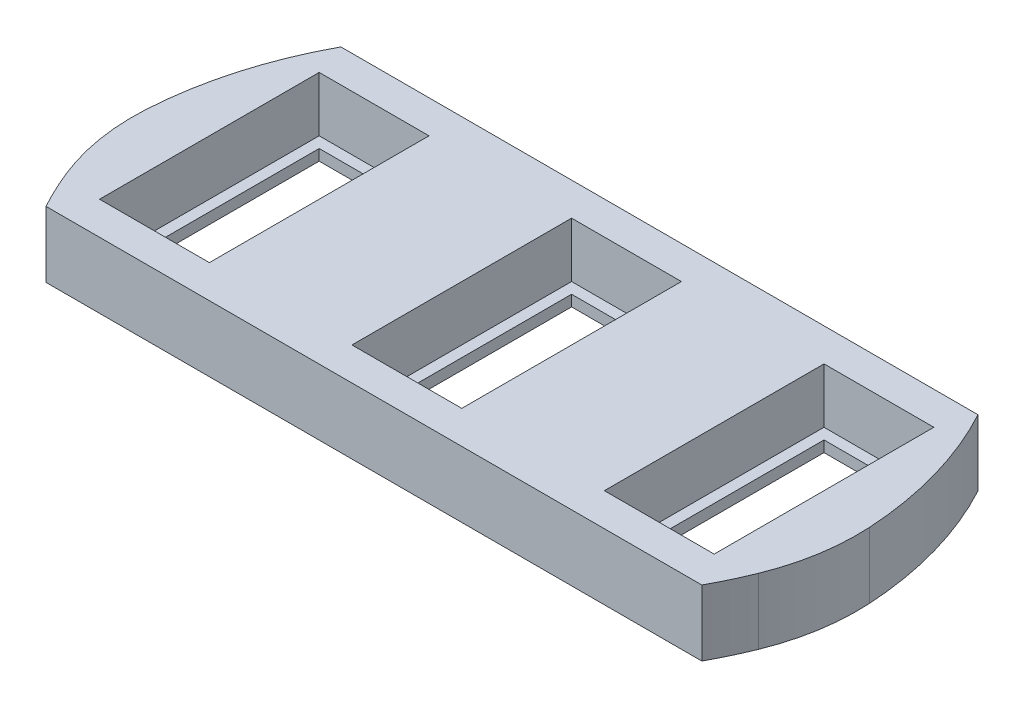
SolidWorks part; units mm, degrees
ref_plane "Plan de face" through (0, 0, 0) normal (0, 0, 1) x (1, 0, 0)
ref_plane "Plan de dessus" through (0, 0, 0) normal (0, 1, 0) x (1, 0, 0)
ref_plane "Plan de droite" through (0, 0, 0) normal (1, 0, 0) x (0, 0, -1)
sketch "Esquisse1" plane through (0, 0, 0) normal (0, 1, 0) x (1, 0, 0)
  line L0 (0, 30.5) -> (0, -31.5) construction
  line L1 (29.005, 12.7388) -> (-29.005, 12.7388)
  line L2 (-29.8592, -13.2612) -> (29.8592, -13.2612)
  line L3 (26.9834, 8.7388) -> (26.9834, -9.2612)
  line L4 (-27.9834, 9.7388) -> (-17.9834, 9.7388) construction
  line L5 (-27.9834, 9.7388) -> (-27.9834, -10.2612) construction
  line L6 (-27.9834, -10.2612) -> (-17.9834, -10.2612) construction
  line L7 (-17.9834, 9.7388) -> (-17.9834, -10.2612) construction
  line L8 (-27.9834, 9.7388) -> (-30.9834, 9.7388) construction
  line L9 (-5, 9.7388) -> (5, 9.7388) construction
  line L10 (-26.9834, 8.7388) -> (-18.9834, 8.7388)
  line L11 (-5, 9.7388) -> (-5, -10.2612) construction
  line L12 (-5, -10.2612) -> (5, -10.2612) construction
  line L13 (5, 9.7388) -> (5, -10.2612) construction
  line L14 (-26.9834, 8.7388) -> (-26.9834, -9.2612)
  line L15 (-26.9834, -9.2612) -> (-18.9834, -9.2612)
  line L16 (-18.9834, 8.7388) -> (-18.9834, -9.2612)
  line L17 (4, 8.7388) -> (-4, 8.7388)
  line L18 (26.9834, 8.7388) -> (18.9834, 8.7388)
  line L19 (4, -9.2612) -> (-4, -9.2612)
  line L20 (-4, 8.7388) -> (-4, -9.2612)
  line L21 (18.9834, 8.7388) -> (18.9834, -9.2612)
  line L22 (26.9834, -9.2612) -> (18.9834, -9.2612)
  line L23 (4, 8.7388) -> (4, -9.2612)
  arc A0 (33.4591, -1.3457) -> (-33.4591, -1.3457) centre (0, -3) ccw construction
  arc A1 (-32.0815, -9.6897) -> (32.0815, -9.6897) centre (0, 3) ccw construction
  arc A2 (-32.0815, -9.6897) -> (-33.4591, -1.3457) centre (-13.4835, -2.3333) cw construction
  arc A3 (32.0815, -9.6897) -> (33.4591, -1.3457) centre (13.4835, -2.3333) ccw construction
  arc A4 (-31.5188, -9.75) -> (-29.8592, -13.2612) centre (0, 3) ccw
  arc A5 (29.005, 12.7388) -> (32.945, -1.0962) centre (0, -3) cw
  arc A6 (-32.945, -1.0962) -> (-31.5188, -9.75) centre (-12.9783, -2.25) ccw
  arc A7 (32.945, -1.0962) -> (31.5188, -9.75) centre (12.9783, -2.25) cw
  arc A8 (-29.005, 12.7388) -> (-32.945, -1.0962) centre (0, -3) ccw
  arc A9 (31.5188, -9.75) -> (29.8592, -13.2612) centre (0, 3) cw
  point P10 (0, -31.5)
  point P11 (0, 30.5)
  point P25 (-22.9834, -9.2612)
  point P26 (-22.9834, 8.7388)
  point P30 (0, 12.7388)
  point P37 (0, 8.7388)
  point P40 (22.9834, 8.7388)
  point P45 (0, -9.2612)
  point P46 (0, 12.5977)
  point P49 (0, -14.4023)
  point P53 (0, -13.2612)
  dimension "D1" = 69
  dimension "D2" = 67
  dimension "D3" = 20
  dimension "D6" = 10
  dimension "D7" = 68
  dimension "D8" = 5
  dimension "D9" = 1
  dimension "D10" = 1
  dimension "D11" = 1
  dimension "D13" = 20
  dimension "D4" = 3
  dimension "D5" = 3
  dimension "D14" = 10
  dimension "D15" = 20
  dimension "D16" = 1
  dimension "D17" = 3
  dimension "D18" = 1
  dimension "D20" = 3
  dimension "D21" = 3
extrude "Boss.-Extru.1" add sketch "Esquisse1" along normal blind 1
sketch "Esquisse2" plane through (0, 1, 0) normal (0, 1, 0) x (1, 0, 0)
  line L0 (-29.005, 12.7388) -> (29.005, 12.7388)
  line L1 (29.8592, -13.2612) -> (0, -13.2612)
  line L2 (-22.9834, 8.7388) -> (-22.9834, -9.2612) construction
  line L3 (-27.9834, 9.7388) -> (-17.9834, 9.7388)
  line L4 (-27.9834, 9.7388) -> (-27.9834, -10.2612)
  line L5 (-27.9834, -10.2612) -> (-17.9834, -10.2612)
  line L6 (-17.9834, 9.7388) -> (-17.9834, -10.2612)
  line L7 (-27.9834, 9.7388) -> (-17.9834, -10.2612) construction
  line L8 (-27.9834, -10.2612) -> (-17.9834, 9.7388) construction
  line L9 (0, -13.2612) -> (-29.8592, -13.2612)
  line L11 (-26.9834, -0.2612) -> (-18.9834, -0.2612) construction
  line L14 (0, 26.0513) -> (0, -22.8455) construction
  line L15 (27.9834, 9.7388) -> (27.9834, -10.2612)
  line L16 (-5, 9.7388) -> (5, 9.7388)
  line L17 (-5, 9.7388) -> (-5, -10.2612)
  line L18 (-5, -10.2612) -> (5, -10.2612)
  line L19 (27.9834, 9.7388) -> (17.9834, 9.7388)
  line L20 (-5, 9.7388) -> (5, -10.2612) construction
  line L21 (-5, -10.2612) -> (5, 9.7388) construction
  line L22 (17.9834, 9.7388) -> (17.9834, -10.2612)
  line L23 (27.9834, -10.2612) -> (17.9834, -10.2612)
  line L24 (5, 9.7388) -> (5, -10.2612)
  line L25 (-26.9834, -9.2612) -> (-18.9834, -9.2612) construction
  line L26 (-18.9834, 8.7388) -> (-26.9834, 8.7388) construction
  line L27 (-18.9834, -9.2612) -> (-18.9834, 8.7388) construction
  line L28 (-26.9834, 8.7388) -> (-26.9834, -9.2612) construction
  arc A0 (-31.5188, -9.75) -> (-29.8592, -13.2612) centre (0, 3) ccw
  arc A1 (32.945, -1.0962) -> (29.005, 12.7388) centre (0, -3) ccw
  arc A4 (-29.005, 12.7388) -> (-32.945, -1.0962) centre (0, -3) ccw
  arc A6 (32.945, -1.0962) -> (29.005, 12.7388) centre (0, -3) ccw construction
  arc A7 (31.5188, -9.75) -> (32.945, -1.0962) centre (12.9783, -2.25) ccw
  arc A8 (-32.945, -1.0962) -> (-31.5188, -9.75) centre (-12.9783, -2.25) ccw
  arc A11 (31.5188, -9.75) -> (32.945, -1.0962) centre (12.9783, -2.25) ccw construction
  arc A12 (29.8592, -13.2612) -> (31.5188, -9.75) centre (0, 3) ccw
  arc A13 (29.8592, -13.2612) -> (31.5188, -9.75) centre (0, 3) ccw construction
  point P9 (-22.9834, -0.2612)
  point P13 (0, -0.2612)
  point P22 (-17.3244, -13.2612)
  point P39 (0, -10.2612)
  point P40 (0, 9.7388)
  point P41 (0, -13.2612)
  point P44 (0, 12.7388)
  point P48 (-0.1955, -13.2612)
  dimension "D1" = 10
  dimension "D2" = 20
  dimension "D3" = 10
extrude "Boss.-Extru.2" add sketch "Esquisse2" along normal blind 5
